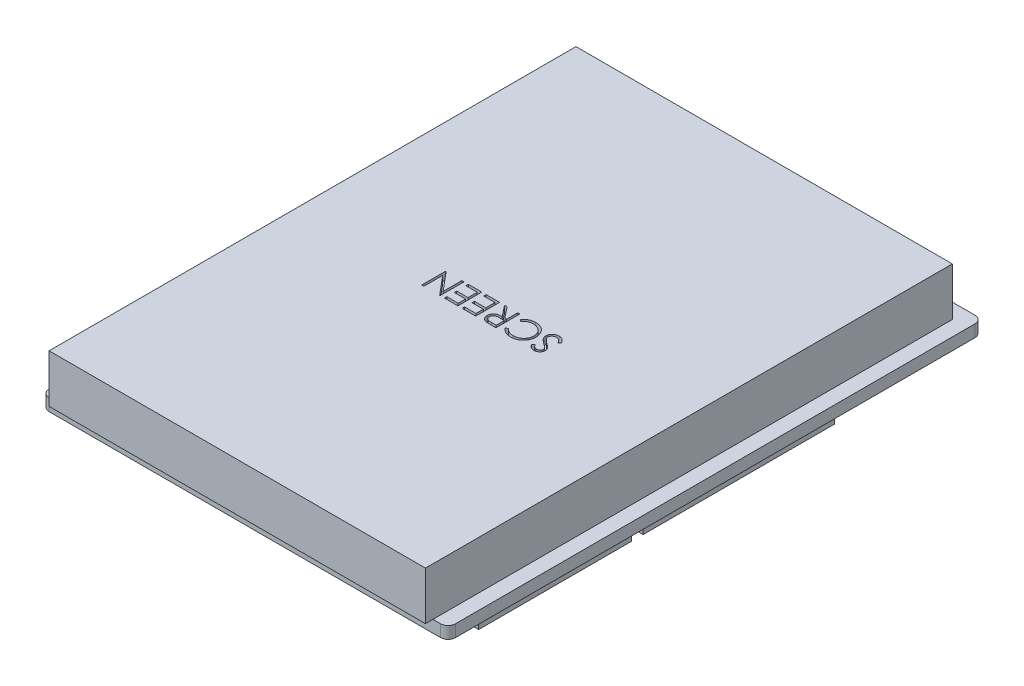
SolidWorks part; units mm, degrees
ref_plane "Front Plane" through (0, 0, 0) normal (0, 0, 1) x (1, 0, 0)
ref_plane "Top Plane" through (0, 0, 0) normal (0, 1, 0) x (1, 0, 0)
ref_plane "Right Plane" through (0, 0, 0) normal (1, 0, 0) x (0, 0, -1)
sketch "Sketch1" plane through (0, 0, 0) normal (0, 1, 0) x (1, 0, 0)
  line L1 (-12.3613, -25.1515) -> (41.6387, -25.1515)
  line L2 (-12.3613, -25.1515) -> (-12.3613, 45.8485)
  line L3 (-12.3613, 45.8485) -> (41.6387, 45.8485)
  line L4 (41.6387, -25.1515) -> (41.6387, 45.8485)
  dimension "D1" = 54
  dimension "D2" = 71
extrude "Boss-Extrude1" add sketch "Sketch1" along normal blind 1.6
fillet "Fillet1" radius 1 1 edges at (-12.3613, 0.8, -45.8485)
fillet "Fillet2" radius 1 1 edges at (41.6387, 0.8, -45.8485)
fillet "Fillet3" radius 1 1 edges at (41.6387, 0.8, 25.1515)
fillet "Fillet4" radius 1 1 edges at (-12.3613, 0.8, 25.1515)
sketch "Sketch2" plane through (0, 1.6, 0) normal (0, 1, 0) x (1, 0, 0)
  line L1 (-10.3613, 43.8485) -> (39.6387, 43.8485)
  line L2 (-10.3613, 43.8485) -> (-10.3613, -26.1515)
  line L3 (-10.3613, -26.1515) -> (39.6387, -26.1515)
  line L4 (39.6387, 43.8485) -> (39.6387, -26.1515)
  line L6 (14.6387, 45.8485) -> (14.6387, -25.1515)
  line L7 (40.6387, 45.8485) -> (-11.3613, 45.8485) construction
  line L8 (-11.3613, -25.1515) -> (40.6387, -25.1515) construction
  point P10 (14.6387, 43.8485)
  dimension "D1" = 50
  dimension "D2" = 70
  dimension "D3" = 0
  dimension "D4" = 1
extrude "Boss-Extrude2" add sketch "Sketch2" along normal blind 6.4 contours L4 L3 L2 L1
sketch "Sketch3" plane through (0, 8, 0) normal (0, 1, 0) x (1, 0, 0)
  line L0 (39.6387, 8.8485) -> (-10.3613, 8.8485)
  line L1 (39.6387, 43.8485) -> (39.6387, -26.1515) construction
  line L2 (-10.3613, 43.8485) -> (-10.3613, -26.1515) construction
  line L3 (22.7797, 8.736) -> (22.5113, 8.5751)
  line L4 (20.948, 6.6295) -> (21.2056, 6.8248)
  line L5 (17.3252, 6.7561) -> (17.5745, 6.9469)
  line L6 (17.5745, 8.5751) -> (17.3252, 8.764)
  line L7 (16.6739, 6.1735) -> (16.0386, 6.1735)
  line L8 (15.8051, 7.8831) -> (14.6387, 9.3485)
  line L9 (14.6387, 9.3485) -> (14.991, 9.3485)
  line L10 (14.991, 9.3485) -> (16.1575, 7.8831)
  line L11 (16.1575, 7.8831) -> (16.389, 7.8831)
  line L12 (16.389, 7.8831) -> (16.389, 9.3485)
  line L13 (16.389, 9.3485) -> (16.6739, 9.3485)
  line L14 (16.6739, 9.3485) -> (16.6739, 6.1735)
  line L15 (16.389, 6.4991) -> (16.389, 7.5574)
  line L16 (16.389, 7.5574) -> (15.8077, 7.5619)
  line L17 (15.7937, 6.4991) -> (16.389, 6.4991)
  line L18 (13.9874, 6.1735) -> (12.1964, 6.1735)
  line L19 (12.1964, 6.1735) -> (12.1964, 6.4991)
  line L20 (12.1964, 6.4991) -> (13.7025, 6.4991)
  line L21 (13.7025, 6.4991) -> (13.7025, 7.476)
  line L22 (13.7025, 7.476) -> (12.1964, 7.476)
  line L23 (12.1964, 7.476) -> (12.1964, 7.8017)
  line L24 (12.1964, 7.8017) -> (13.7025, 7.8017)
  line L25 (13.7025, 7.8017) -> (13.7025, 9.0228)
  line L26 (13.7025, 9.0228) -> (12.1964, 9.0228)
  line L27 (12.1964, 9.0228) -> (12.1964, 9.3485)
  line L28 (12.1964, 9.3485) -> (13.9874, 9.3485)
  line L29 (13.9874, 9.3485) -> (13.9874, 6.1735)
  line L30 (11.6265, 6.1735) -> (9.8355, 6.1735)
  line L31 (9.8355, 6.1735) -> (9.8355, 6.4991)
  line L32 (9.8355, 6.4991) -> (11.3416, 6.4991)
  line L33 (11.3416, 6.4991) -> (11.3416, 7.476)
  line L34 (11.3416, 7.476) -> (9.8355, 7.476)
  line L35 (9.8355, 7.476) -> (9.8355, 7.8017)
  line L36 (9.8355, 7.8017) -> (11.3416, 7.8017)
  line L37 (11.3416, 7.8017) -> (11.3416, 9.0228)
  line L38 (11.3416, 9.0228) -> (9.8355, 9.0228)
  line L39 (9.8355, 9.0228) -> (9.8355, 9.3485)
  line L40 (9.8355, 9.3485) -> (11.6265, 9.3485)
  line L41 (11.6265, 9.3485) -> (11.6265, 6.1735)
  line L42 (9.2656, 9.3485) -> (9.2656, 6.1735)
  line L43 (9.2656, 6.1735) -> (9.2058, 6.1735)
  line L44 (9.2058, 6.1735) -> (7.1082, 8.6724)
  line L45 (7.1082, 8.6724) -> (7.1082, 6.1735)
  line L46 (7.1082, 6.1735) -> (6.8233, 6.1735)
  line L47 (6.8233, 6.1735) -> (6.8233, 9.3485)
  line L48 (6.8233, 9.3485) -> (6.8882, 9.3485)
  line L49 (6.8882, 9.3485) -> (8.9807, 6.8553)
  line L50 (8.9807, 6.8553) -> (8.9807, 9.3485)
  line L51 (8.9807, 9.3485) -> (9.2656, 9.3485)
  spline S0 degree 3 poles (22.5113, 8.5751) (22.4648, 8.6558) (22.3914, 8.7689) (22.276, 8.897) (22.1899, 8.9723) (22.1007, 9.0314) (21.9783, 9.0871) (21.8795, 9.1044) (21.8142, 9.1042) knots 0 0 0 0 0.304646 0.438547 0.562322 0.677433 0.786897 1 1 1 1
  spline S1 degree 3 poles (21.8142, 9.1042) (21.7591, 9.1045) (21.6765, 9.0956) (21.5712, 9.0636) (21.4961, 9.0315) (21.4264, 8.9919) (21.3644, 8.9453) (21.312, 8.8914) (21.2687, 8.8322) (21.2348, 8.7689) (21.2025, 8.6814) (21.1922, 8.6122) (21.1922, 8.5662) knots 0 0 0 0 0.18101 0.270405 0.360513 0.448738 0.532675 0.614376 0.694559 0.772714 0.849123 1 1 1 1
  spline S2 degree 3 poles (21.1922, 8.5662) (21.1916, 8.5125) (21.2142, 8.4006) (21.271, 8.3019) (21.3061, 8.2545) knots 0 0 0 0 0.475391 1 1 1 1
  spline S3 degree 3 poles (21.3061, 8.2545) (21.335, 8.2154) (21.3857, 8.1581) (21.4613, 8.0824) (21.5292, 8.0209) (21.6047, 7.956) (21.7209, 7.8632) (21.8135, 7.7942) (21.8785, 7.7483) knots 0 0 0 0 0.190099 0.299187 0.418362 0.548359 0.688775 1 1 1 1
  spline S4 degree 3 poles (21.8785, 7.7483) (21.9426, 7.7032) (22.0328, 7.6367) (22.1449, 7.5495) (22.2156, 7.4937) (22.2752, 7.4417) (22.3378, 7.3859) (22.3768, 7.3435) (22.3987, 7.3164) knots 0 0 0 0 0.347075 0.495559 0.629077 0.745524 0.845834 1 1 1 1
  spline S5 degree 3 poles (22.3987, 7.3164) (22.4268, 7.28) (22.466, 7.2243) (22.5076, 7.1448) (22.5323, 7.0847) (22.5523, 7.0236) (22.571, 6.94) (22.5764, 6.8758) (22.5762, 6.833) knots 0 0 0 0 0.26255 0.388252 0.511531 0.633734 0.755402 1 1 1 1
  spline S6 degree 3 poles (22.5762, 6.833) (22.5764, 6.7665) (22.5637, 6.6678) (22.5217, 6.543) (22.4769, 6.4562) (22.4214, 6.3757) (22.3556, 6.303) (22.2782, 6.2405) (22.1921, 6.1873) (22.0989, 6.1449) (21.9672, 6.1032) (21.8633, 6.0928) (21.7939, 6.0921) knots 0 0 0 0 0.16577 0.246266 0.327682 0.408711 0.489625 0.571615 0.656207 0.741698 0.826557 1 1 1 1
  spline S7 degree 3 poles (21.7939, 6.0921) (21.7196, 6.0915) (21.6085, 6.1065) (21.4673, 6.1542) (21.3825, 6.1965) (21.3161, 6.2383) (21.2656, 6.2764) (21.214, 6.3203) (21.1621, 6.3707) (21.1093, 6.4267) (21.0358, 6.512) (20.9825, 6.5808) (20.948, 6.6295) knots 0 0 0 0 0.212613 0.318547 0.426489 0.48333 0.543275 0.607966 0.677192 0.750736 0.828748 1 1 1 1
  spline S8 degree 3 poles (21.2056, 6.8248) (21.2351, 6.7858) (21.2799, 6.7313) (21.3394, 6.6627) (21.3819, 6.6199) (21.4208, 6.5805) (21.4592, 6.5473) (21.4957, 6.5194) (21.5416, 6.4896) (21.5999, 6.4607) (21.6971, 6.4272) (21.7743, 6.4179) (21.8257, 6.4177) knots 0 0 0 0 0.189596 0.274136 0.352122 0.4237 0.48904 0.548952 0.60191 0.70128 0.800434 1 1 1 1
  spline S9 degree 3 poles (21.8257, 6.4177) (21.8889, 6.4165) (21.9812, 6.4308) (22.0925, 6.4798) (22.162, 6.531) (22.2194, 6.5921) (22.2759, 6.6853) (22.2911, 6.7663) (22.2912, 6.8197) knots 0 0 0 0 0.275822 0.401869 0.527875 0.650459 0.765964 1 1 1 1
  spline S10 degree 3 poles (22.2912, 6.8197) (22.2919, 6.8539) (22.2854, 6.905) (22.2665, 6.9713) (22.2465, 7.0209) (22.2193, 7.0716) (22.1671, 7.1445) (22.1178, 7.1955) (22.082, 7.2299) knots 0 0 0 0 0.21612 0.323407 0.434613 0.553299 0.685993 1 1 1 1
  spline S11 degree 3 poles (22.082, 7.2299) (22.0657, 7.2449) (22.0358, 7.2694) (21.9885, 7.3047) (21.94, 7.3415) (21.882, 7.3842) (21.7858, 7.4527) (21.7096, 7.5078) (21.6552, 7.546) knots 0 0 0 0 0.124952 0.218094 0.333502 0.468789 0.624938 1 1 1 1
  spline S12 degree 3 poles (21.6552, 7.546) (21.5884, 7.5944) (21.4919, 7.6654) (21.373, 7.7639) (21.2955, 7.8332) (21.2258, 7.8999) (21.1645, 7.9648) (21.1116, 8.0274) (21.0537, 8.1072) (20.9954, 8.2061) (20.9295, 8.3645) (20.9073, 8.4889) (20.9073, 8.5706) knots 0 0 0 0 0.187763 0.272381 0.351302 0.424312 0.491882 0.554203 0.610843 0.715918 0.81455 1 1 1 1
  spline S13 degree 3 poles (20.9073, 8.5706) (20.9064, 8.6271) (20.9156, 8.7106) (20.9426, 8.8186) (20.9722, 8.8956) (21.0094, 8.97) (21.0546, 9.0417) (21.1094, 9.1095) (21.1703, 9.1748) (21.2379, 9.2339) (21.3094, 9.2865) (21.3845, 9.3315) (21.464, 9.3669) (21.5466, 9.3951) (21.6628, 9.4227) (21.7533, 9.4301) (21.8142, 9.4299) knots 0 0 0 0 0.121779 0.180926 0.240265 0.299715 0.360503 0.423144 0.488 0.553287 0.616917 0.679809 0.742178 0.804656 0.868254 1 1 1 1
  spline S14 degree 3 poles (21.8142, 9.4299) (21.8619, 9.4301) (21.9325, 9.4246) (22.0252, 9.4086) (22.092, 9.3907) (22.1576, 9.3683) (22.2212, 9.341) (22.283, 9.3084) (22.3432, 9.2706) (22.4023, 9.227) (22.46, 9.1766) (22.5166, 9.1198) (22.5724, 9.0565) (22.626, 8.9858) (22.6984, 8.8802) (22.7477, 8.7951) (22.7797, 8.736) knots 0 0 0 0 0.1137 0.168686 0.224158 0.278721 0.333797 0.389247 0.4454 0.503285 0.564258 0.627941 0.694626 0.765364 0.839605 1 1 1 1
  spline S15 degree 3 poles (17.5745, 6.9469) (17.6092, 6.9043) (17.6642, 6.8433) (17.7437, 6.7691) (17.8053, 6.7171) (17.8706, 6.6706) (17.9372, 6.6259) (18.0075, 6.5869) (18.1042, 6.5391) (18.2312, 6.4904) (18.4463, 6.4335) (18.6148, 6.4172) (18.7283, 6.4177) knots 0 0 0 0 0.125464 0.187105 0.248272 0.309267 0.370082 0.431199 0.492677 0.616182 0.740867 1 1 1 1
  spline S16 degree 3 poles (18.7283, 6.4177) (18.7917, 6.4169) (18.886, 6.4236) (19.0099, 6.4421) (19.1005, 6.4618) (19.1889, 6.4875) (19.2759, 6.5177) (19.3604, 6.5552) (19.4436, 6.5967) (19.5232, 6.6435) (19.5985, 6.6946) (19.6693, 6.7494) (19.7356, 6.8078) (19.7968, 6.8705) (19.8536, 6.9368) (19.9058, 7.0069) (19.9535, 7.0806) (19.9961, 7.1575) (20.0331, 7.2372) (20.0643, 7.3194) (20.0897, 7.404) (20.1095, 7.4907) (20.1281, 7.6106) (20.1346, 7.7023) (20.1339, 7.7642) knots 0 0 0 0 0.087505 0.130468 0.173045 0.215416 0.257665 0.300169 0.34314 0.385945 0.427707 0.468841 0.509517 0.549704 0.589803 0.629994 0.670459 0.710976 0.751344 0.791767 0.832452 0.873314 0.91454 1 1 1 1
  spline S17 degree 3 poles (20.1339, 7.7642) (20.1343, 7.8563) (20.1215, 7.9925) (20.0799, 8.1676) (20.0349, 8.2906) (19.9782, 8.4082) (19.9074, 8.519) (19.8252, 8.6246) (19.7306, 8.7224) (19.6268, 8.8118) (19.5155, 8.8905) (19.3968, 8.9561) (19.2722, 9.0107) (19.1406, 9.0526) (18.9532, 9.0929) (18.8074, 9.105) (18.7086, 9.1042) knots 0 0 0 0 0.126289 0.186724 0.246417 0.305584 0.365437 0.426333 0.488846 0.55173 0.613923 0.675488 0.737337 0.800231 0.864504 1 1 1 1
  spline S18 degree 3 poles (18.7086, 9.1042) (18.5995, 9.1043) (18.4376, 9.0889) (18.2309, 9.0327) (18.0845, 8.9748) (17.9455, 8.8994) (17.7663, 8.7757) (17.6478, 8.6593) (17.5745, 8.5751) knots 0 0 0 0 0.252949 0.374755 0.49594 0.617181 0.740909 1 1 1 1
  spline S19 degree 3 poles (17.3252, 8.764) (17.3645, 8.8162) (17.4269, 8.8912) (17.5185, 8.9828) (17.5905, 9.0465) (17.6663, 9.1058) (17.7459, 9.1604) (17.8288, 9.2109) (17.9152, 9.2566) (18.005, 9.2973) (18.0976, 9.3329) (18.193, 9.3628) (18.2906, 9.3879) (18.3913, 9.4058) (18.5296, 9.4252) (18.6355, 9.43) (18.7066, 9.4299) knots 0 0 0 0 0.123065 0.183492 0.243749 0.304061 0.364651 0.425398 0.486849 0.548684 0.611128 0.673519 0.736958 0.800714 0.866 1 1 1 1
  spline S20 degree 3 poles (18.7066, 9.4299) (18.7742, 9.4307) (18.8741, 9.4253) (19.0051, 9.4112) (19.0992, 9.3955) (19.1909, 9.3771) (19.2794, 9.3523) (19.3656, 9.3246) (19.449, 9.2921) (19.5298, 9.2553) (19.6077, 9.2138) (19.6826, 9.1678) (19.7554, 9.1184) (19.8249, 9.064) (19.9146, 8.9854) (19.9771, 8.9206) (20.0162, 8.8746) knots 0 0 0 0 0.13775 0.203917 0.26878 0.332414 0.394754 0.45618 0.516996 0.577396 0.637198 0.696999 0.756756 0.816554 0.876948 1 1 1 1
  spline S21 degree 3 poles (20.0162, 8.8746) (20.082, 8.7978) (20.1705, 8.6746) (20.2638, 8.4966) (20.3209, 8.3576) (20.3646, 8.2123) (20.4065, 8.0077) (20.4191, 7.8494) (20.4188, 7.7425) knots 0 0 0 0 0.247152 0.368774 0.490247 0.61362 0.738962 1 1 1 1
  spline S22 degree 3 poles (20.4188, 7.7425) (20.4188, 7.6303) (20.4048, 7.4637) (20.3528, 7.2504) (20.3002, 7.0991) (20.2307, 6.9553) (20.1466, 6.8182) (20.047, 6.688) (19.9332, 6.5665) (19.8084, 6.4553) (19.6748, 6.3575) (19.5326, 6.2761) (19.3833, 6.2081) (19.226, 6.1558) (19.0023, 6.106) (18.8282, 6.0923) (18.7105, 6.0921) knots 0 0 0 0 0.127011 0.18795 0.247928 0.307764 0.368249 0.429483 0.492755 0.556268 0.618226 0.679663 0.741252 0.80342 0.866819 1 1 1 1
  spline S23 degree 3 poles (18.7105, 6.0921) (18.6383, 6.0919) (18.5311, 6.0968) (18.391, 6.1159) (18.2895, 6.1351) (18.1904, 6.1589) (18.0941, 6.1888) (18.0009, 6.2249) (17.9102, 6.2651) (17.8231, 6.3112) (17.7397, 6.3612) (17.6606, 6.4162) (17.5853, 6.4754) (17.5143, 6.5392) (17.4234, 6.6292) (17.3635, 6.7046) (17.3252, 6.7561) knots 0 0 0 0 0.135659 0.201179 0.265635 0.329596 0.392594 0.454885 0.517294 0.578946 0.639886 0.699999 0.759849 0.81966 0.879376 1 1 1 1
  spline S24 degree 3 poles (16.0386, 6.1735) (15.9572, 6.1739) (15.8405, 6.1737) (15.6921, 6.1797) (15.5969, 6.1835) (15.5123, 6.1903) (15.4205, 6.1982) (15.3574, 6.2082) (15.3192, 6.2167) knots 0 0 0 0 0.338434 0.484822 0.617158 0.734698 0.837385 1 1 1 1
  spline S25 degree 3 poles (15.3192, 6.2167) (15.273, 6.2269) (15.2057, 6.2481) (15.1208, 6.2856) (15.061, 6.3184) (15.0046, 6.3558) (14.9515, 6.3978) (14.9025, 6.4449) (14.8558, 6.4951) (14.815, 6.5506) (14.7783, 6.6086) (14.7474, 6.6701) (14.7232, 6.7349) (14.7028, 6.8023) (14.6842, 6.8981) (14.6792, 6.9723) (14.6794, 7.0226) knots 0 0 0 0 0.12704 0.188709 0.249085 0.309868 0.370231 0.430629 0.492277 0.554095 0.615218 0.676315 0.738476 0.800796 0.86521 1 1 1 1
  spline S26 degree 3 poles (14.6794, 7.0226) (14.6791, 7.1049) (14.6931, 7.2273) (14.7473, 7.379) (14.802, 7.4825) (14.8717, 7.5759) (14.9554, 7.6577) (15.0527, 7.7267) (15.1438, 7.7741) (15.2242, 7.8045) (15.2907, 7.8261) (15.3632, 7.8425) (15.4408, 7.8573) (15.524, 7.8687) (15.6459, 7.8798) (15.7404, 7.8829) (15.8051, 7.8831) knots 0 0 0 0 0.153711 0.226699 0.299172 0.371166 0.442978 0.516334 0.592857 0.63351 0.676624 0.722915 0.771971 0.823829 0.879386 1 1 1 1
  spline S27 degree 3 poles (15.8077, 7.5619) (15.7551, 7.5627) (15.6789, 7.56) (15.581, 7.5542) (15.5156, 7.5479) (15.4557, 7.5398) (15.4014, 7.5296) (15.3524, 7.5178) (15.2956, 7.4993) (15.2313, 7.4714) (15.1629, 7.428) (15.1031, 7.3755) (15.0533, 7.3148) (15.0134, 7.2477) (14.9759, 7.1511) (14.9638, 7.0739) (14.9643, 7.0219) knots 0 0 0 0 0.138878 0.201133 0.259059 0.312176 0.36059 0.404983 0.444989 0.518418 0.589383 0.657995 0.727586 0.795841 0.863197 1 1 1 1
  spline S28 degree 3 poles (14.9643, 7.0219) (14.9643, 6.9714) (14.9754, 6.8955) (15.0145, 6.8016) (15.0543, 6.7359) (15.1039, 6.6767) (15.1616, 6.6262) (15.2261, 6.5843) (15.286, 6.5566) (15.3399, 6.5403) (15.3864, 6.5285) (15.4395, 6.5202) (15.4985, 6.5126) (15.5636, 6.5061) (15.6626, 6.5002) (15.74, 6.4989) (15.7937, 6.4991) knots 0 0 0 0 0.136311 0.203719 0.273225 0.342608 0.411062 0.479239 0.549585 0.587914 0.630892 0.679007 0.732608 0.791193 0.85534 1 1 1 1
extrude "Cut-Extrude1" cut sketch "Sketch3" against normal blind 1 contours L24 L25 L26 L27 L28 L29 L18 L19 L20 L21 L22 L23 | L36 L37 L38 L39 L40 L41 L30 L31 L32 L33 L34 L35 | L44 L45 L46 L47 L48 L49 L50 L51 L42 L43 | L14 L7 S24 S25 S26 L8 L9 L10 L11 L12 L13 | L15 L16 S27 S28 L17 | S21 S22 S23 L5 S15 S16 S17 S18 L6 S19 S20 | S12 S13 S14 L3 S0 S1 S2 S3 S4 S5 S6 S7 L4 S8 S9 S10 S11
sketch "Sketch4" plane through (0, 0, 0) normal (0, -1, 0) x (1, 0, 0)
  line L0 (-12.3613, -44.8485) -> (-12.3613, 24.1515) construction
  line L1 (-11.0913, 19.1515) -> (-8.5513, 19.1515)
  line L2 (-11.0913, 19.1515) -> (-11.0913, 3.9115)
  line L3 (-11.0913, 3.9115) -> (-8.5513, 3.9115)
  line L4 (-8.5513, 19.1515) -> (-8.5513, 3.9115)
  line L5 (-11.0913, 1.3715) -> (-8.5513, 1.3715)
  line L6 (-11.0913, 1.3715) -> (-11.0913, -18.9485)
  line L7 (-11.0913, -18.9485) -> (-8.5513, -18.9485)
  line L8 (-8.5513, 1.3715) -> (-8.5513, -18.9485)
  line L9 (37.1687, -28.0925) -> (39.7087, -28.0925)
  line L10 (37.1687, -28.0925) -> (37.1687, -2.6925)
  line L11 (37.1687, -2.6925) -> (39.7087, -2.6925)
  line L12 (39.7087, -28.0925) -> (39.7087, -2.6925)
  line L13 (37.1687, -1.1685) -> (39.7087, -1.1685)
  line L14 (37.1687, -1.1685) -> (37.1687, 19.1515)
  line L15 (37.1687, 19.1515) -> (39.7087, 19.1515)
  line L16 (39.7087, -1.1685) -> (39.7087, 19.1515)
  line L17 (41.6387, 24.1515) -> (41.6387, -44.8485) construction
  line L18 (-11.3613, 25.1515) -> (40.6387, 25.1515) construction
  line L19 (40.6387, -45.8485) -> (-11.3613, -45.8485) construction
  dimension "D1" = 2.54
  dimension "D2" = 2.54
  dimension "D3" = 2.54
  dimension "D4" = 2.54
  dimension "D5" = 15.24
  dimension "D6" = 20.32
  dimension "D7" = 20.32
  dimension "D8" = 25.4
  dimension "D9" = 2.54
  dimension "D10" = 1.524
  dimension "D11" = 0
  dimension "D12" = 45.72
  dimension "D13" = 1.27
  dimension "D14" = 1.93
  dimension "D15" = 54
  dimension "D16" = 0
  dimension "D17" = 0
  dimension "D18" = 6
  dimension "D19" = 26.9
extrude "Boss-Extrude3" add sketch "Sketch4" along normal blind 2.54 contours L2 L3 L4 L1 | L6 L7 L8 L5 | L14 L15 L16 L13 | L10 L11 L12 L9
